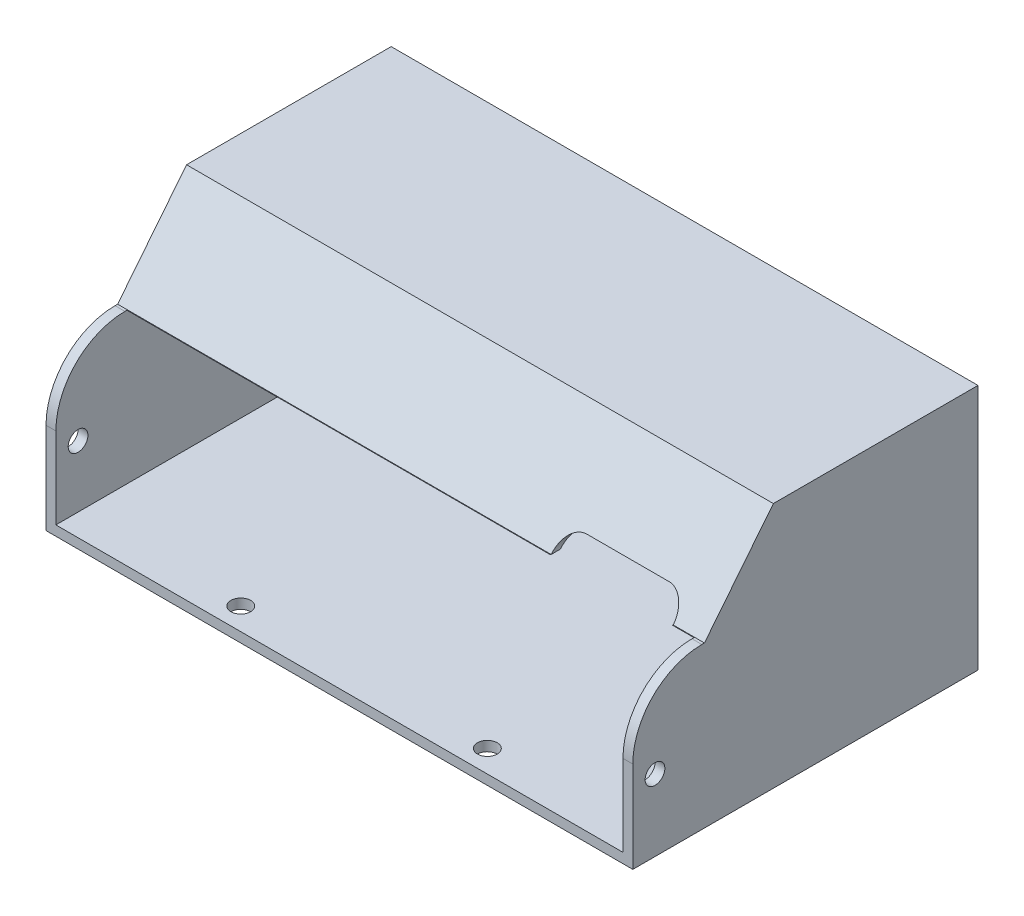
SolidWorks part; units mm, degrees
ref_plane "Front Plane" through (0, 0, 0) normal (0, 0, 1) x (1, 0, 0)
ref_plane "Top Plane" through (0, 0, 0) normal (0, 1, 0) x (1, 0, 0)
ref_plane "Right Plane" through (0, 0, 0) normal (1, 0, 0) x (0, 0, -1)
sketch "Sketch1" plane through (0, 0, 0) normal (0, 0, 1) x (1, 0, 0)
  line L1 (0, 0) -> (119, 0)
  line L2 (0, 0) -> (0, 50)
  line L3 (0, 50) -> (119, 50)
  line L4 (119, 0) -> (119, 50)
  line L5 (0, 0) -> (119, 50) construction
  line L6 (0, 50) -> (119, 0) construction
  point P4 (59.5, 25)
  dimension "D1" = 119
  dimension "D2" = 50
extrude "Boss-Extrude1" add sketch "Sketch1" along normal blind 70
sketch "Sketch2" plane through (0, 0, 70) normal (0, 0, 1) x (1, 0, 0)
  line L0 (119, 50) -> (0, 50) construction
  line L1 (2, 48) -> (117, 48)
  line L2 (2, 48) -> (2, 2)
  line L3 (2, 2) -> (117, 2)
  line L4 (117, 48) -> (117, 2)
  line L5 (2, 48) -> (117, 2) construction
  line L6 (2, 2) -> (117, 48) construction
  line L7 (0, 50) -> (0, 0) construction
  line L8 (119, 0) -> (119, 50) construction
  line L9 (0, 0) -> (119, 0) construction
  point P4 (59.5, 25)
  dimension "D1" = 2
  dimension "D2" = 2
  dimension "D3" = 2
  dimension "D4" = 2
extrude "Cut-Extrude1" cut sketch "Sketch2" against normal offset from surface (67 mm away) 3 up to face at (59.5, 25, 0)
sketch "Sketch3" plane through (0, 0, 3) normal (0, 0, 1) x (1, 0, 0)
  line L0 (2, 25) -> (117, 25) construction
  line L1 (8, 39.5) -> (58, 39.5)
  line L2 (8, 39.5) -> (8, 10.5)
  line L3 (8, 10.5) -> (58, 10.5)
  line L4 (58, 39.5) -> (58, 10.5)
  line L5 (8, 39.5) -> (58, 10.5) construction
  line L6 (8, 10.5) -> (58, 39.5) construction
  line L7 (2, 48) -> (2, 2) construction
  line L8 (117, 2) -> (117, 48) construction
  point P4 (33, 25)
  point P11 (0, 0)
  dimension "D1" = 50
  dimension "D2" = 29
  dimension "D3" = 8
extrude "Cut-Extrude2" cut sketch "Sketch3" against normal blind 10
sketch "Sketch4" plane through (0, 0, 0) normal (0, 0, -1) x (-1, 0, 0)
  circle A0 centre (-32.95, 45) radius 1.95
  circle A1 centre (-32.95, 5) radius 1.95
  dimension "D1" = 3.9
  dimension "D2" = 3.9
extrude "Cut-Extrude3" cut sketch "Sketch4" against normal blind 10
sketch "Sketch5" plane through (0, 0, 3) normal (0, 0, 1) x (1, 0, 0)
  circle A0 centre (32.95, 45) radius 3.25
  circle A1 centre (32.95, 45) radius 1.95
  circle A2 centre (32.95, 5) radius 3.25
  circle A3 centre (32.95, 5) radius 1.95
  dimension "D1" = 6.5
  dimension "D2" = 6.5
extrude "Boss-Extrude3" add sketch "Sketch5" along normal blind 10
fillet "Fillet1" radius 2 2 edges at (32.95, 8.25, 3) (32.95, 41.75, 3)
sketch "Sketch6" plane through (0, 2, 0) normal (0, 1, 0) x (1, 0, 0)
  circle A0 centre (85, -65.5) radius 2
  circle A1 centre (35, -65.5) radius 2
extrude "Cut-Extrude4" cut sketch "Sketch6" against normal blind 10
sketch "Sketch8" plane through (2, 0, 0) normal (1, 0, 0) x (0, 0, -1)
  circle A0 centre (-65.5, 14.5) radius 2
extrude "Cut-Extrude5" cut sketch "Sketch8" against normal through all both and the other way through all
sketch "Sketch9" plane through (2, 0, 0) normal (1, 0, 0) x (0, 0, -1)
  line L0 (-55.5941, 32.5006) -> (-43.1696, 48)
  line L1 (-3, 48) -> (-70, 48) construction
  line L2 (-43.1696, 48) -> (-41.1696, 48)
  line L3 (-55.5941, 32.5006) -> (-53.5941, 32.4994)
  line L4 (-53.5941, 32.4994) -> (-41.1696, 48)
  point P4 (-41.3379, 48)
  point P5 (-41.1696, 48)
  point P8 (0, 0)
  point P9 (-54.5941, 32.5)
  dimension "D1" = 2
  dimension "D2" = 2
  dimension "D3" = 15.5
extrude "Boss-Extrude4" add sketch "Sketch9" along normal up to surface (115 mm away) up to face at (117, 14.5, 63.5)
sketch "Sketch10" plane through (2, 0, 0) normal (1, 0, 0) x (0, 0, -1)
  line L0 (-55.4718, 32.5006) -> (-70, 32.5006)
  line L1 (-70, 48) -> (-70, 2) construction
  line L2 (-70, 32.5006) -> (-70, 50)
  line L3 (-70, 50) -> (-41.5, 50)
  line L4 (-70, 50) -> (0, 50) construction
  line L5 (-41.5, 50) -> (-55.4718, 32.5006)
  point P4 (-41.6223, 50)
  dimension "D1" = 28.5
extrude "Cut-Extrude6" cut sketch "Sketch10" against normal through all both and the other way through all
fillet "Fillet2" radius 14 2 edges at (1, 32.5006, 70) (118, 32.5006, 70)
sketch "Sketch11" plane through (0, 0, 0) normal (0, 0, -1) x (-1, 0, 0)
  line L0 (-111, 45) -> (-111, 5) construction
  line L1 (-109.2028, 45) -> (-109.2028, 5)
  line L2 (-112.7972, 45) -> (-112.7972, 5)
  line L3 (-119, 50) -> (0, 50) construction
  line L4 (0, 0) -> (-119, 0) construction
  line L5 (-119, 0) -> (-119, 50) construction
  line L6 (-104, 45) -> (-104, 5) construction
  line L7 (-102.2028, 45) -> (-102.2028, 5)
  line L8 (-105.7972, 45) -> (-105.7972, 5)
  line L9 (-97, 45) -> (-97, 5) construction
  line L10 (-95.2028, 45) -> (-95.2028, 5)
  line L11 (-98.7972, 45) -> (-98.7972, 5)
  line L12 (-90, 45) -> (-90, 5) construction
  line L13 (-88.2028, 45) -> (-88.2028, 5)
  line L14 (-91.7972, 45) -> (-91.7972, 5)
  line L15 (-83, 45) -> (-83, 5) construction
  line L16 (-81.2028, 45) -> (-81.2028, 5)
  line L17 (-84.7972, 45) -> (-84.7972, 5)
  line L18 (-76, 45) -> (-76, 5) construction
  line L19 (-74.2028, 45) -> (-74.2028, 5)
  line L20 (-77.7972, 45) -> (-77.7972, 5)
  line L21 (-69, 45) -> (-69, 5) construction
  line L22 (-67.2028, 45) -> (-67.2028, 5)
  line L23 (-70.7972, 45) -> (-70.7972, 5)
  arc A0 (-109.2028, 45) -> (-112.7972, 45) centre (-111, 45) ccw
  arc A1 (-112.7972, 5) -> (-109.2028, 5) centre (-111, 5) ccw
  arc A2 (-102.2028, 45) -> (-105.7972, 45) centre (-104, 45) ccw
  arc A3 (-105.7972, 5) -> (-102.2028, 5) centre (-104, 5) ccw
  arc A4 (-95.2028, 45) -> (-98.7972, 45) centre (-97, 45) ccw
  arc A5 (-98.7972, 5) -> (-95.2028, 5) centre (-97, 5) ccw
  arc A6 (-88.2028, 45) -> (-91.7972, 45) centre (-90, 45) ccw
  arc A7 (-91.7972, 5) -> (-88.2028, 5) centre (-90, 5) ccw
  arc A8 (-81.2028, 45) -> (-84.7972, 45) centre (-83, 45) ccw
  arc A9 (-84.7972, 5) -> (-81.2028, 5) centre (-83, 5) ccw
  arc A10 (-74.2028, 45) -> (-77.7972, 45) centre (-76, 45) ccw
  arc A11 (-77.7972, 5) -> (-74.2028, 5) centre (-76, 5) ccw
  arc A12 (-67.2028, 45) -> (-70.7972, 45) centre (-69, 45) ccw
  arc A13 (-70.7972, 5) -> (-67.2028, 5) centre (-69, 5) ccw
  point P2 (-111, 25)
  point P16 (-104, 25)
  point P23 (-97, 25)
  point P30 (-90, 25)
  point P37 (-83, 25)
  point P44 (-76, 25)
  point P51 (-69, 25)
  dimension "D1" = 5
  dimension "D2" = 5
  dimension "D3" = 8
  dimension "D4" = 7
extrude "Cut-Extrude8" cut sketch "Sketch11" against normal blind 10
ref_plane "Plane1" through (0, 0, 10) normal (0, 0, 1) x (1, 0, 0)
sketch "Sketch12" plane through (0, 0, 10) normal (0, 0, 1) x (1, 0, 0)
  line L0 (108.6674, 32.4994) -> (91.9107, 32.4994) construction
  line L1 (117, 32.4994) -> (2, 32.4994) construction
  line L2 (108.6674, 28.4994) -> (91.9107, 28.4994)
  line L3 (108.6674, 36.4994) -> (91.9107, 36.4994)
  arc A0 (108.6674, 28.4994) -> (108.6674, 36.4994) centre (108.6674, 32.4994) ccw
  arc A1 (91.9107, 36.4994) -> (91.9107, 28.4994) centre (91.9107, 32.4994) ccw
  point P4 (100.2891, 32.4994)
  dimension "D1" = 4
extrude "Cut-Extrude9" cut sketch "Sketch12" along normal through all
